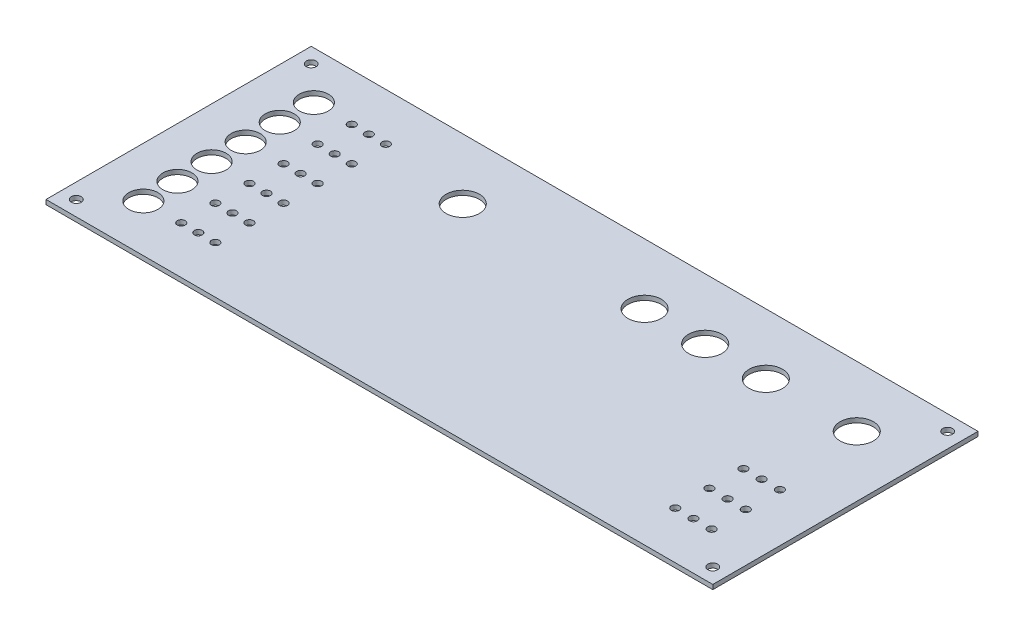
SolidWorks part; units mm, degrees
ref_plane "Front Plane" through (0, 0, 0) normal (0, 0, 1) x (1, 0, 0)
ref_plane "Top Plane" through (0, 0, 0) normal (0, 1, 0) x (1, 0, 0)
ref_plane "Right Plane" through (0, 0, 0) normal (1, 0, 0) x (0, 0, -1)
sketch "Sketch1" plane through (0, 0, 0) normal (0, 1, 0) x (1, 0, 0)
  line L0 (420, 20) -> (20, 20) construction
  line L1 (440, 175) -> (0, 175)
  line L2 (440, 175) -> (440, 0)
  line L3 (440, 0) -> (0, 0)
  line L4 (0, 175) -> (0, 0)
  line L5 (20, 155) -> (20, 20) construction
  line L6 (420, 155) -> (20, 155) construction
  line L7 (420, 155) -> (420, 20) construction
  line L9 (20, 143.75) -> (120, 143.75) construction
  line L10 (33, 20) -> (33, 155) construction
  line L11 (20, 121.25) -> (120, 121.25) construction
  line L12 (58, 20) -> (58, 155) construction
  line L13 (120, 98.75) -> (20, 98.75) construction
  line L14 (69.25, 20) -> (69.25, 155) construction
  line L15 (20, 76.25) -> (420, 76.25) construction
  line L16 (80.5, 20) -> (80.5, 155) construction
  line L17 (420, 53.75) -> (20, 53.75) construction
  line L19 (20, 31.25) -> (420, 31.25) construction
  line L20 (420, 135) -> (140, 135) construction
  circle A0 centre (10, 10) radius 3.25
  circle A1 centre (10, 165) radius 3.25
  circle A2 centre (430, 165) radius 3.25
  circle A3 centre (430, 10) radius 3.25
  circle A4 centre (33, 31.25) radius 9.6
  circle A5 centre (33, 53.75) radius 9.6
  circle A6 centre (33, 76.25) radius 9.6
  circle A7 centre (33, 98.75) radius 9.6
  circle A8 centre (33, 121.25) radius 9.6
  circle A9 centre (33, 143.75) radius 9.6
  circle A10 centre (33, 31.25) radius 11 construction
  circle A11 centre (33, 53.75) radius 11 construction
  circle A12 centre (58, 31.25) radius 2.6
  circle A13 centre (58, 53.75) radius 2.6
  circle A14 centre (58, 76.25) radius 2.6
  circle A15 centre (58, 98.75) radius 2.6
  circle A16 centre (58, 121.25) radius 2.6
  circle A17 centre (58, 143.75) radius 2.6
  circle A18 centre (69.25, 31.25) radius 2.6
  circle A19 centre (69.25, 53.75) radius 2.6
  circle A20 centre (69.25, 76.25) radius 2.6
  circle A21 centre (69.25, 98.75) radius 2.6
  circle A22 centre (69.25, 121.25) radius 2.6
  circle A23 centre (69.25, 143.75) radius 2.6
  circle A24 centre (80.5, 31.25) radius 2.6
  circle A25 centre (80.5, 53.75) radius 2.6
  circle A26 centre (80.5, 76.25) radius 2.6
  circle A27 centre (80.5, 98.75) radius 2.6
  circle A28 centre (80.5, 121.25) radius 2.6
  circle A29 centre (80.5, 143.75) radius 2.6
  circle A30 centre (400, 135) radius 11
  circle A31 centre (340, 135) radius 11
  circle A32 centre (300, 135) radius 11
  circle A33 centre (260, 135) radius 11
  circle A34 centre (140, 135) radius 11
  circle A35 centre (408, 31.25) radius 2.6
  circle A36 centre (396, 31.25) radius 2.6
  circle A37 centre (384, 31.25) radius 2.6
  circle A38 centre (408, 53.75) radius 2.6
  circle A39 centre (396, 53.75) radius 2.6
  circle A40 centre (384, 53.75) radius 2.6
  circle A41 centre (408, 76.25) radius 2.6
  circle A42 centre (396, 76.25) radius 2.6
  circle A43 centre (384, 76.25) radius 2.6
  dimension "D1" = 135
  dimension "D2" = 400
  dimension "D3" = 22.5
  dimension "D4" = 22.5
  dimension "D5" = 22.5
  dimension "D6" = 22.5
  dimension "D7" = 22.5
  dimension "D8" = 11.25
  dimension "D9" = 11.25
  dimension "D10" = 11.25
  dimension "D11" = 25
  dimension "D12" = 13
  dimension "D13" = 20
  dimension "D14" = 12
  dimension "D15" = 12
  dimension "D16" = 12
  dimension "D17" = 20
  dimension "D18" = 60
  dimension "D19" = 40
  dimension "D20" = 40
  dimension "D21" = 120
extrude "Boss-Extrude1" add sketch "Sketch1" along normal blind 3
